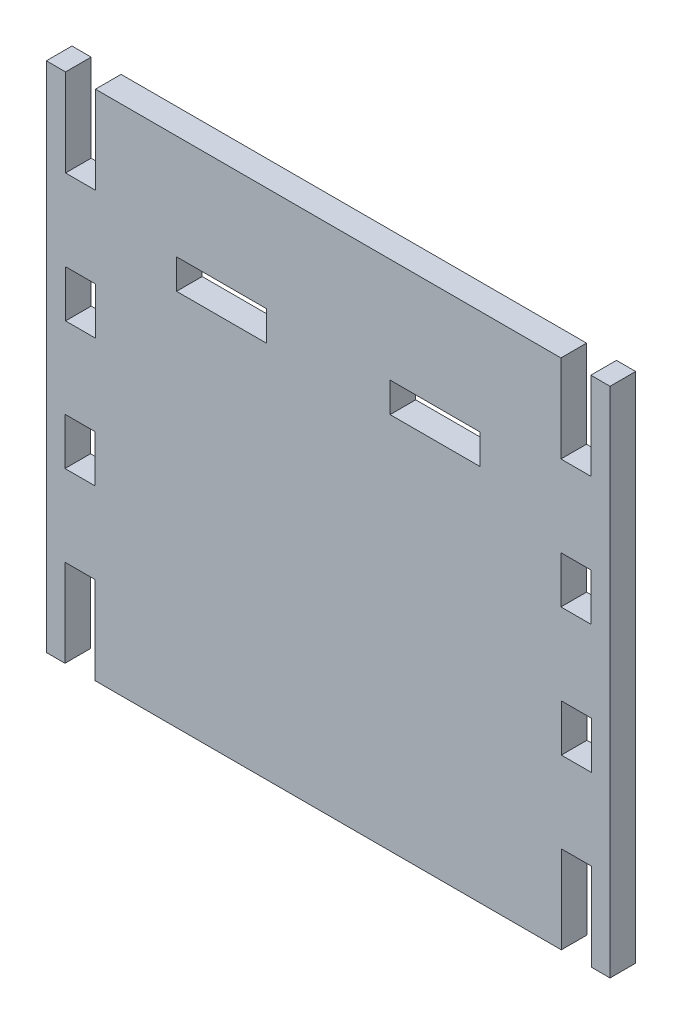
SolidWorks part; units mm, degrees
ref_plane "Спереди" through (0, 0, 0) normal (0, 0, 1) x (1, 0, 0)
ref_plane "Сверху" through (0, 0, 0) normal (0, 1, 0) x (1, 0, 0)
ref_plane "Справа" through (0, 0, 0) normal (1, 0, 0) x (0, 0, -1)
sketch "Эскиз1" plane through (0, 0, 0) normal (0, 0, 1) x (1, 0, 0)
  line L0 (0, 14.5) -> (0, 18.3638) construction
  line L1 (-17.75, 17.75) -> (-7.25, 17.75)
  line L2 (-17.75, 17.75) -> (-17.75, 14.25)
  line L3 (-17.75, 14.25) -> (-7.25, 14.25)
  line L4 (-7.25, 17.75) -> (-7.25, 14.25)
  line L5 (-27.25, 30) -> (27.25, 30)
  line L6 (-30.75, 30) -> (-30.75, 19.75)
  line L7 (-30.75, 19.75) -> (-27.25, 19.75)
  line L8 (-27.25, 30) -> (-27.25, 19.75)
  line L9 (-30.75, 10.25) -> (-27.25, 10.25)
  line L10 (-30.75, 10.25) -> (-30.75, 4.75)
  line L11 (-30.75, 4.75) -> (-27.25, 4.75)
  line L12 (-27.25, 10.25) -> (-27.25, 4.75)
  line L13 (-30.8168, -4.75) -> (-27.2966, -4.75)
  line L14 (-30.8168, -4.75) -> (-30.8168, -10.25)
  line L15 (-30.8168, -10.25) -> (-27.2966, -10.25)
  line L16 (-27.2966, -4.75) -> (-27.2966, -10.25)
  line L17 (-30.8168, -19.75) -> (-27.2966, -19.75)
  line L18 (-30.8168, -19.75) -> (-30.8168, -30)
  line L19 (33, 30) -> (33, -30)
  line L20 (-27.2966, -19.75) -> (-27.2966, -30)
  line L21 (33, 30) -> (30.75, 30)
  line L22 (-33, 30) -> (-30.75, 30)
  line L23 (-33, 30) -> (-33, -30)
  line L24 (-33, -30) -> (-30.8168, -30)
  line L25 (27.2966, -19.75) -> (27.2966, -30)
  line L26 (30.8168, -19.75) -> (30.8168, -30)
  line L27 (30.8168, -19.75) -> (27.2966, -19.75)
  line L28 (27.2966, -4.75) -> (27.2966, -10.25)
  line L29 (30.8168, -10.25) -> (27.2966, -10.25)
  line L30 (30.8168, -4.75) -> (30.8168, -10.25)
  line L31 (30.8168, -4.75) -> (27.2966, -4.75)
  line L32 (27.25, 10.25) -> (27.25, 4.75)
  line L33 (30.75, 4.75) -> (27.25, 4.75)
  line L34 (30.75, 10.25) -> (30.75, 4.75)
  line L35 (30.75, 10.25) -> (27.25, 10.25)
  line L36 (27.25, 30) -> (27.25, 19.75)
  line L37 (30.75, 19.75) -> (27.25, 19.75)
  line L38 (30.75, 30) -> (30.75, 19.75)
  line L39 (7.25, 17.75) -> (7.25, 14.25)
  line L40 (17.75, 14.25) -> (7.25, 14.25)
  line L41 (17.75, 17.75) -> (17.75, 14.25)
  line L42 (17.75, 17.75) -> (7.25, 17.75)
  line L43 (30.8168, -30) -> (33, -30)
  line L44 (-27.2966, -30) -> (27.2966, -30)
  point P27 (0, -30)
  point P44 (0, 30)
  dimension "D1" = 3.5
  dimension "D2" = 10.25
  dimension "D3" = 10.5
  dimension "D4" = 3.5
  dimension "D5" = 12.25
  dimension "D6" = 5.5
  dimension "D7" = 9.5
  dimension "D8" = 5.5
  dimension "D9" = 9.5
  dimension "D10" = 10.25
extrude "Бобышка-Вытянуть1" add sketch "Эскиз1" along normal blind 3
